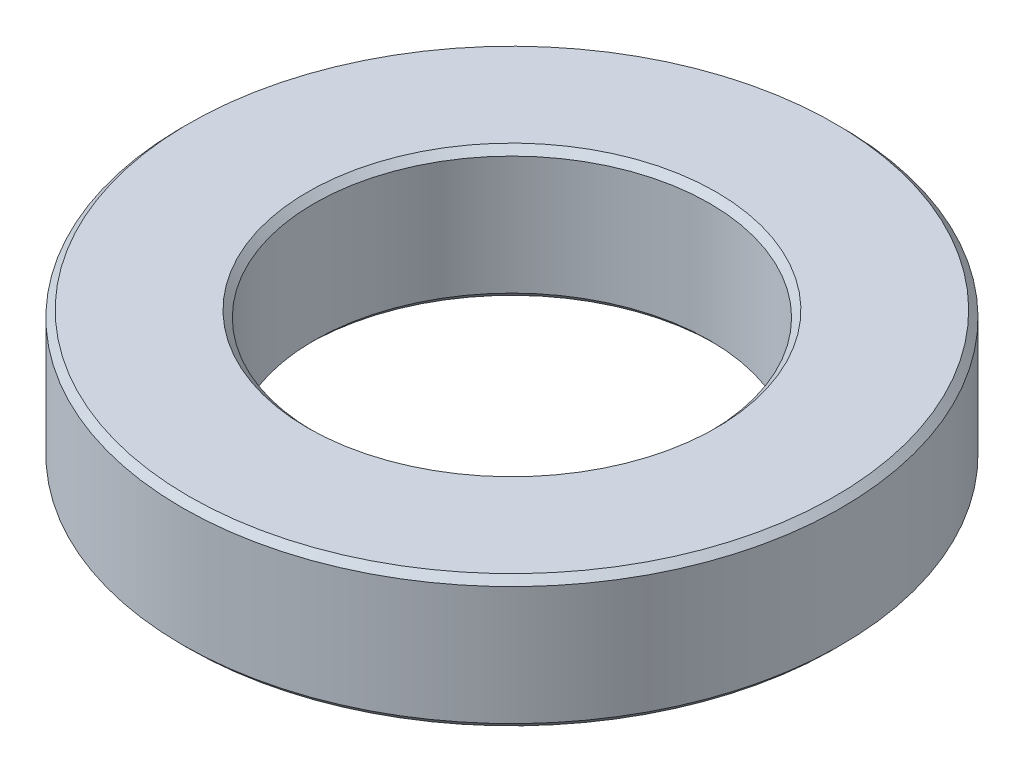
SolidWorks part; units mm, degrees
material "尼龙 6/10"
ref_plane "前视基准面" through (0, 0, 0) normal (0, 0, 1) x (1, 0, 0)
ref_plane "上视基准面" through (0, 0, 0) normal (0, 1, 0) x (1, 0, 0)
ref_plane "右视基准面" through (0, 0, 0) normal (1, 0, 0) x (0, 0, -1)
sketch "草图1" plane through (0, 0, 0) normal (0, 1, 0) x (1, 0, 0)
  circle A0 centre (0, 0) radius 5
  circle A1 centre (0, 0) radius 3
  dimension "D1" = 6
  dimension "D2" = 10
extrude "凸台-拉伸1" add sketch "草图1" along normal blind 2
chamfer "倒角1" distance 0.1 angle 45 4 edges at (0, 0, 3) (0, 2, 3) (0, 0, 5) (0, 2, 5)
